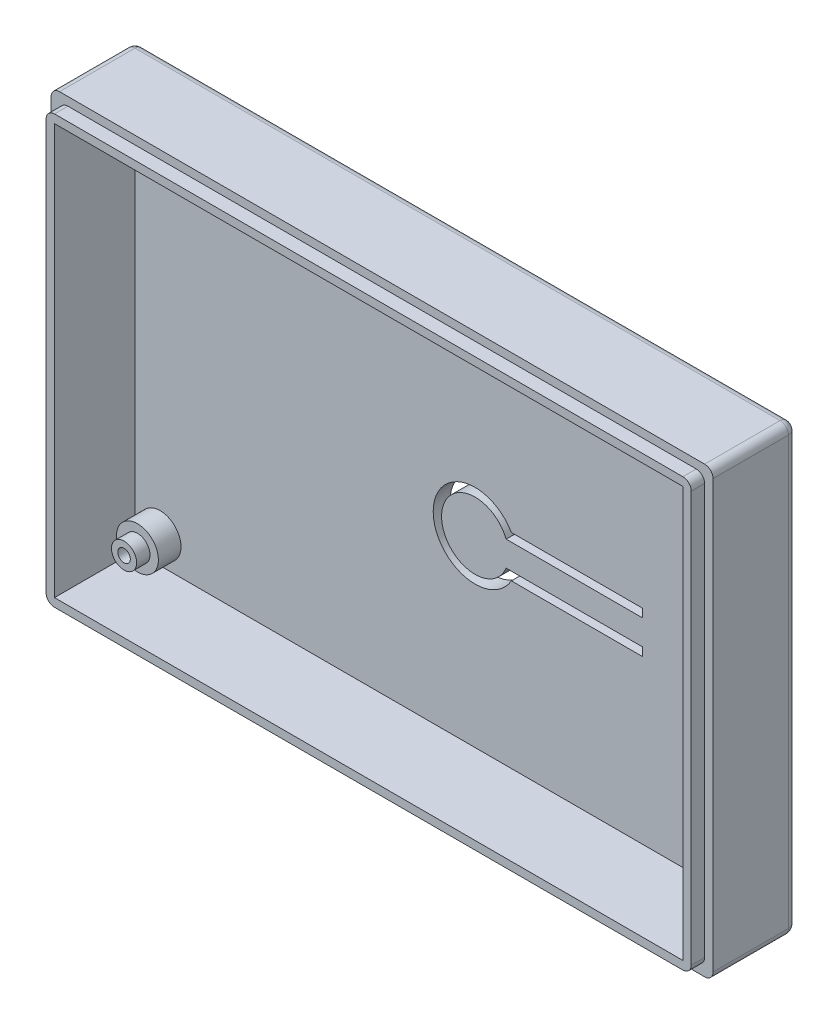
SolidWorks part; units mm, degrees
ref_plane "Front Plane" through (0, 0, 0) normal (0, 0, 1) x (1, 0, 0)
ref_plane "Top Plane" through (0, 0, 0) normal (0, 1, 0) x (1, 0, 0)
ref_plane "Right Plane" through (0, 0, 0) normal (1, 0, 0) x (0, 0, -1)
sketch "Sketch1" plane through (0, 0, 0) normal (0, 0, 1) x (1, 0, 0)
  line L1 (0, 0) -> (79, 0)
  line L2 (0, 0) -> (0, 53)
  line L3 (0, 53) -> (79, 53)
  line L4 (79, 0) -> (79, 53)
  dimension "D1" = 53
  dimension "D2" = 79
extrude "Boss-Extrude1" add sketch "Sketch1" along normal blind 2
sketch "Sketch2" plane through (0, 0, 2) normal (0, 0, 1) x (1, 0, 0)
  line L0 (39.5, 53) -> (39.5, 47.8) construction
  line L1 (5, 5.2) -> (74, 5.2) construction
  line L2 (5, 5.2) -> (5, 47.8) construction
  line L3 (5, 47.8) -> (74, 47.8) construction
  line L4 (74, 5.2) -> (74, 47.8) construction
  line L5 (79, 53) -> (0, 53) construction
  line L6 (5, 26.5) -> (0, 26.5) construction
  line L7 (0, 53) -> (0, 0) construction
  circle A0 centre (5, 47.8) radius 2.5
  circle A1 centre (74, 47.8) radius 2.5
  circle A2 centre (74, 5.2) radius 2.5
  circle A3 centre (5, 5.2) radius 2.5
  dimension "D1" = 5
  dimension "D2" = 42.6
  dimension "D3" = 69
extrude "Boss-Extrude2" add sketch "Sketch2" along normal blind 2.7
sketch "Sketch3" plane through (0, 0, 4.7) normal (0, 0, 1) x (1, 0, 0)
  circle A0 centre (5, 47.8) radius 1.5
  circle A1 centre (5, 5.2) radius 1.5
  circle A2 centre (74, 47.8) radius 1.5
  circle A3 centre (74, 5.2) radius 1.5
  circle A4 centre (5, 47.8) radius 2.5 construction
  circle A5 centre (5, 5.2) radius 2.5 construction
  circle A6 centre (74, 47.8) radius 2.5 construction
  circle A7 centre (74, 5.2) radius 2.5 construction
  dimension "D1" = 3
extrude "Boss-Extrude3" add sketch "Sketch3" along normal blind 1.6
sketch "Sketch5" plane through (0, 0, 6.3) normal (0, 0, 1) x (1, 0, 0)
  circle A0 centre (74, 5.2) radius 0.75
  circle A1 centre (74, 47.8) radius 0.75
  circle A2 centre (5, 47.8) radius 0.75
  circle A3 centre (5, 5.2) radius 0.75
  circle A4 centre (74, 5.2) radius 1.5 construction
  circle A5 centre (74, 47.8) radius 1.5 construction
  circle A6 centre (5, 5.2) radius 1.5 construction
  circle A7 centre (5, 47.8) radius 1.5 construction
  dimension "D1" = 1.5
extrude "Cut-Extrude1" cut sketch "Sketch5" against normal blind 2
sketch "Sketch6" plane through (0, 0, 2) normal (0, 0, 1) x (1, 0, 0)
  line L0 (0, 53) -> (0, 0) construction
  line L1 (79, 53) -> (0, 53) construction
  line L2 (79, 0) -> (79, 53) construction
  line L3 (0, 0) -> (79, 0) construction
  line L4 (0, 53) -> (0, 0)
  line L5 (79, 53) -> (0, 53)
  line L6 (79, 0) -> (79, 53)
  line L7 (0, 0) -> (79, 0)
  line L8 (2, 2) -> (77, 2)
  line L9 (77, 2) -> (77, 51)
  line L10 (77, 51) -> (2, 51)
  line L11 (2, 51) -> (2, 2)
  dimension "D1" = 2
extrude "Boss-Extrude4" add sketch "Sketch6" along normal blind 8
sketch "Sketch7" plane through (0, 0, 10) normal (0, 0, 1) x (1, 0, 0)
  line L0 (2, 51) -> (2, 2) construction
  line L1 (77, 51) -> (2, 51) construction
  line L2 (77, 2) -> (77, 51) construction
  line L3 (2, 2) -> (77, 2) construction
  line L4 (2, 51) -> (2, 2)
  line L5 (77, 51) -> (2, 51)
  line L6 (77, 2) -> (77, 51)
  line L7 (2, 2) -> (77, 2)
  line L8 (1, 1) -> (78, 1)
  line L9 (78, 1) -> (78, 52)
  line L10 (78, 52) -> (1, 52)
  line L11 (1, 52) -> (1, 1)
  dimension "D1" = 1
extrude "Boss-Extrude5" add sketch "Sketch7" along normal blind 1.6
sketch "Sketch8" plane through (0, 0, 2) normal (0, 0, 1) x (1, 0, 0)
  line L0 (46.9301, 21.4) -> (62.6, 21.4)
  line L1 (74, 5.2) -> (5, 5.2) construction
  line L2 (74, 5.2) -> (74, 47.8) construction
  line L3 (74, 47.8) -> (5, 47.8) construction
  line L4 (5, 5.2) -> (5, 47.8) construction
  line L5 (62.6, 21.4) -> (62.6, 22.4)
  line L6 (62.6, 22.4) -> (46.3081, 22.4)
  line L7 (42.6, 23.9) -> (74, 23.9) construction
  line L8 (62.6, 26.4) -> (62.6, 25.4)
  line L9 (62.6, 25.4) -> (46.3081, 25.4)
  line L10 (46.9301, 26.4) -> (62.6, 26.4)
  arc A0 (46.3081, 25.4) -> (46.3081, 22.4) centre (42.6, 23.9) ccw
  arc A1 (46.9301, 26.4) -> (46.9301, 21.4) centre (42.6, 23.9) ccw
  circle A3 centre (42.6, 23.9) radius 5 construction
  circle A4 centre (42.6, 23.9) radius 4 construction
  point P7 (0, 0)
  point P9 (40.3689, 26.0771)
  point P12 (54.454, 22.4)
  point P20 (0, 0)
  point P21 (0, 0)
  point P22 (41.5, 25.2)
  dimension "D1" = 37.6
  dimension "D3" = 8
  dimension "D2" = 18.7
  dimension "D5" = 1
  dimension "D7" = 1.5
  dimension "D6" = 20
  dimension "D4" = 1
extrude "Cut-Extrude2" cut sketch "Sketch8" against normal blind 2
fillet "Fillet1" radius 1 12 edges at (79, 53, 5) (1, 52, 10.8) (0, 53, 5) (1, 1, 10.8) (0, 0, 5) (79, 0, 5) (78, 1, 10.8) (78, 52, 10.8) (39.5, 0, 0) (0, 26.5, 0) (39.5, 53, 0) (79, 26.5, 0)
